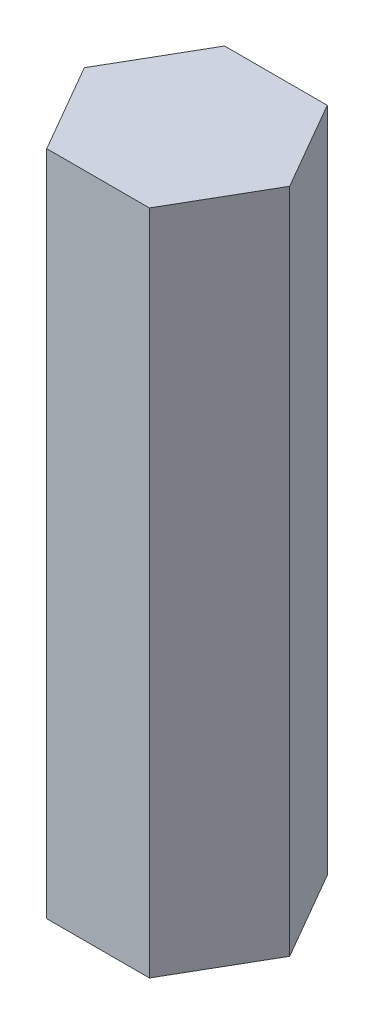
SolidWorks part; units mm, degrees
material "Brass"
ref_plane "Front Plane" through (0, 0, 0) normal (0, 0, 1) x (1, 0, 0)
ref_plane "Top Plane" through (0, 0, 0) normal (0, 1, 0) x (1, 0, 0)
ref_plane "Right Plane" through (0, 0, 0) normal (1, 0, 0) x (0, 0, -1)
sketch "Sketch1" plane through (0, 0, 0) normal (0, 1, 0) x (1, 0, 0)
  line L1 (-14.6647, 0) -> (-7.3323, -12.7)
  line L2 (-7.3323, -12.7) -> (7.3323, -12.7)
  line L3 (7.3323, -12.7) -> (14.6647, 0)
  line L4 (14.6647, 0) -> (7.3323, 12.7)
  line L5 (7.3323, 12.7) -> (-7.3323, 12.7)
  line L6 (-7.3323, 12.7) -> (-14.6647, 0)
  circle A0 centre (0, 0) radius 12.7 construction
  dimension "D1" = 25.4
extrude "Boss-Extrude1" add sketch "Sketch1" along normal mid plane 95.25
